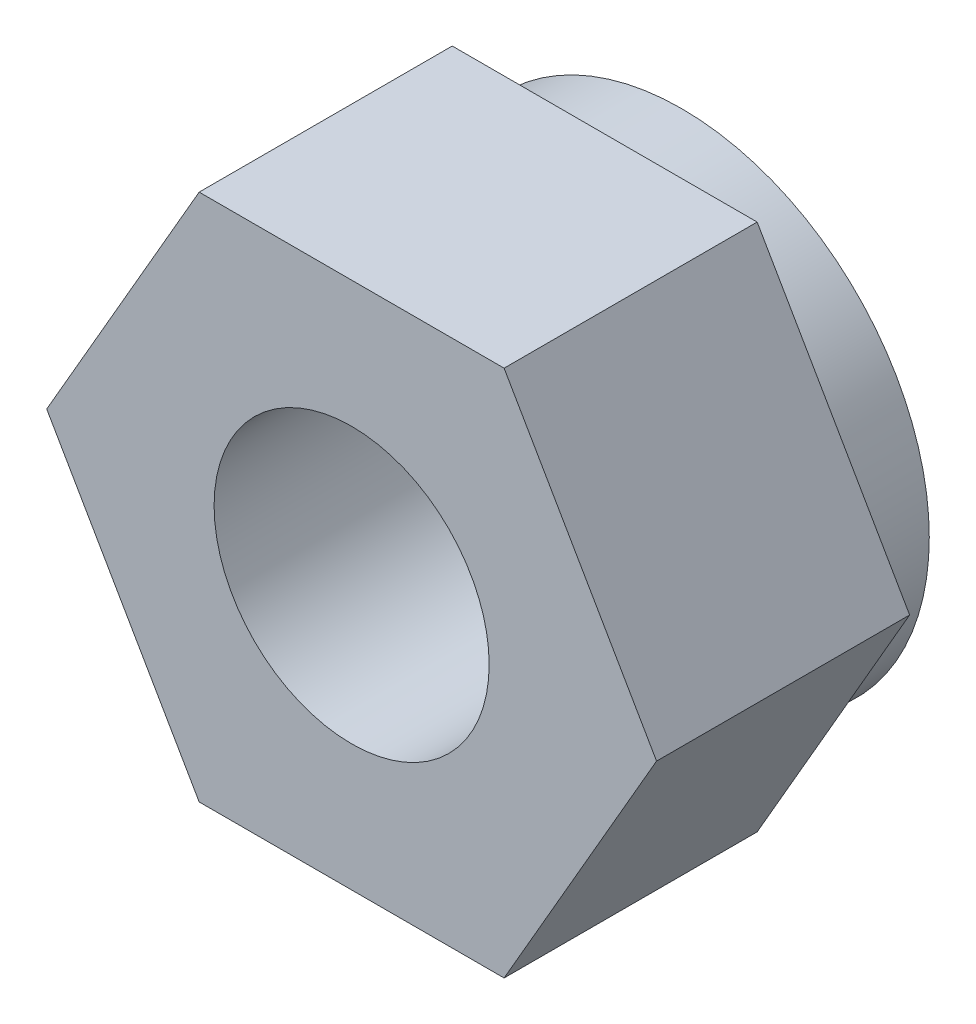
SolidWorks part; units mm, degrees
material "AISI 304"
ref_plane "前视基准面" through (0, 0, 0) normal (0, 0, 1) x (1, 0, 0)
ref_plane "上视基准面" through (0, 0, 0) normal (0, 1, 0) x (1, 0, 0)
ref_plane "右视基准面" through (0, 0, 0) normal (1, 0, 0) x (0, 0, -1)
sketch "草图1" plane through (0, 0, 0) normal (0, 0, 1) x (1, 0, 0)
  line L1 (-1.3856, 2.4) -> (-2.7713, 0)
  line L2 (-2.7713, 0) -> (-1.3856, -2.4)
  line L3 (-1.3856, -2.4) -> (1.3856, -2.4)
  line L4 (1.3856, -2.4) -> (2.7713, 0)
  line L5 (2.7713, 0) -> (1.3856, 2.4)
  line L6 (1.3856, 2.4) -> (-1.3856, 2.4)
  circle A0 centre (0, 0) radius 2.4 construction
  circle A1 centre (0, 0) radius 1.25
  dimension "D2" = 2.5
  dimension "D1" = 4.8
extrude "凸台-拉伸1" add sketch "草图1" along normal blind 2.3
sketch "草图2" plane through (0, 0, 0) normal (0, 0, -1) x (-1, 0, 0)
  circle A0 centre (0, 0) radius 2.25
  circle A1 centre (0, 0) radius 1.25 construction
  circle A2 centre (0, 0) radius 1.25
  dimension "D1" = 4.5
extrude "凸台-拉伸2" add sketch "草图2" along normal blind 0.7
